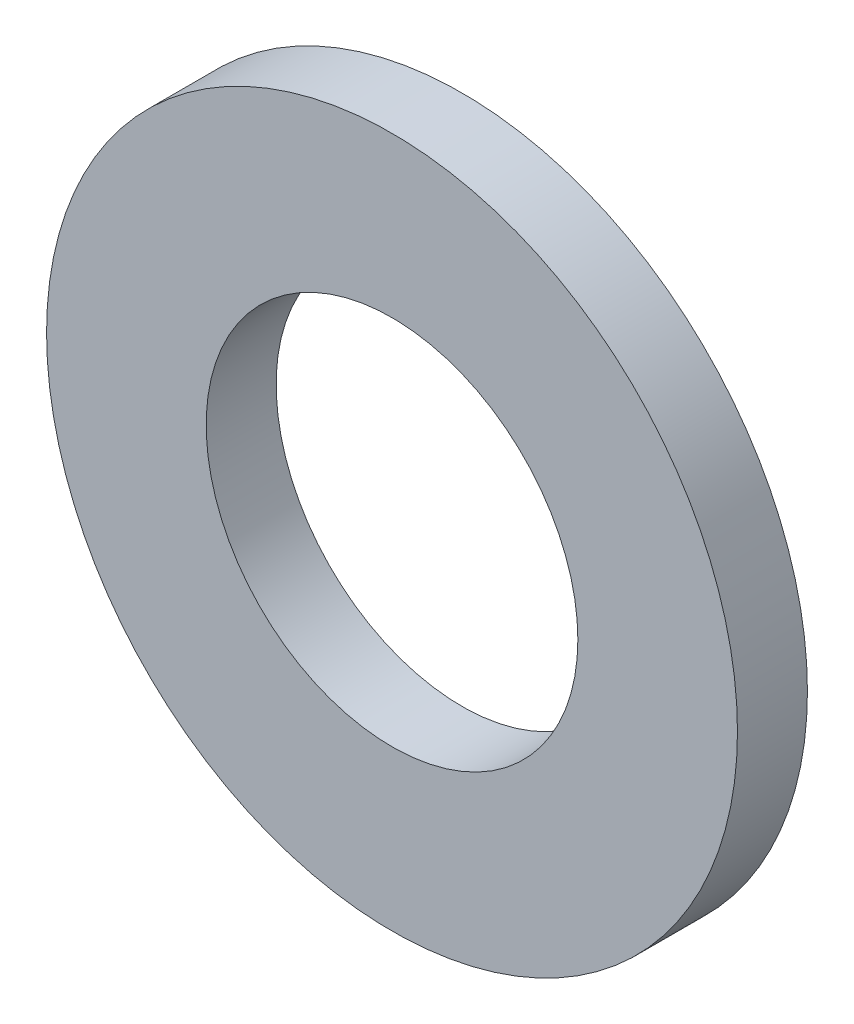
SolidWorks part; units mm, degrees
ref_plane "Front Plane" through (0, 0, 0) normal (0, 0, 1) x (1, 0, 0)
ref_plane "Top Plane" through (0, 0, 0) normal (0, 1, 0) x (1, 0, 0)
ref_plane "Right Plane" through (0, 0, 0) normal (1, 0, 0) x (0, 0, -1)
sketch "Sketch1" plane through (0, 0, 0) normal (0, 0, 1) x (1, 0, 0)
  circle A0 centre (0, 0) radius 7.9 construction
  circle A1 centre (0, 0) radius 4.25 construction
  point P5 (-4.25, 0)
  point P6 (4.25, 0)
  point P7 (7.9, 0)
  point P8 (-7.9, 0)
  dimension "OD" = 15.8
  dimension "ID" = 8.5
sketch "Sketch2" plane through (0, 0, 0) normal (1, 0, 0) x (0, 0, -1)
  line L0 (0.8, 0) -> (-0.8, 0) construction
  line L1 (0, 7.9) -> (0, -7.9) construction
  line L2 (0, 7.9) -> (0, -7.9) construction
  line L3 (0.8, 7.9) -> (-0.8, 7.9) construction
  line L4 (0.8, -7.9) -> (-0.8, -7.9) construction
  line L5 (-0.8, -7.9) -> (-0.8, 7.9) construction
  line L6 (0.8, -7.9) -> (0.8, 7.9) construction
  point P4 (0, 0)
  point P10 (0, 7.9)
  point P11 (-0.8, 7.9)
  point P14 (0, -7.9)
  point P15 (-0.8, -7.9)
  point P16 (0.8, -7.9)
  point P17 (0.8, 7.9)
  point P18 (0.8, 0)
  point P19 (-0.8, 0)
  dimension "Thickness" = 1.6
sketch "Sketch3" plane through (0, 0, 0) normal (0, 0, 1) x (1, 0, 0)
  circle A0 centre (0, 0) radius 7.9 construction
  circle A1 centre (0, 0) radius 4.25 construction
  circle A2 centre (0, 0) radius 7.9
  circle A3 centre (0, 0) radius 4.25
extrude "Boss-Extrude1" add sketch "Sketch3" along normal mid plane 1.6
equation "\"D1@Boss-Extrude1\"=\"Thickness@Sketch2\""
